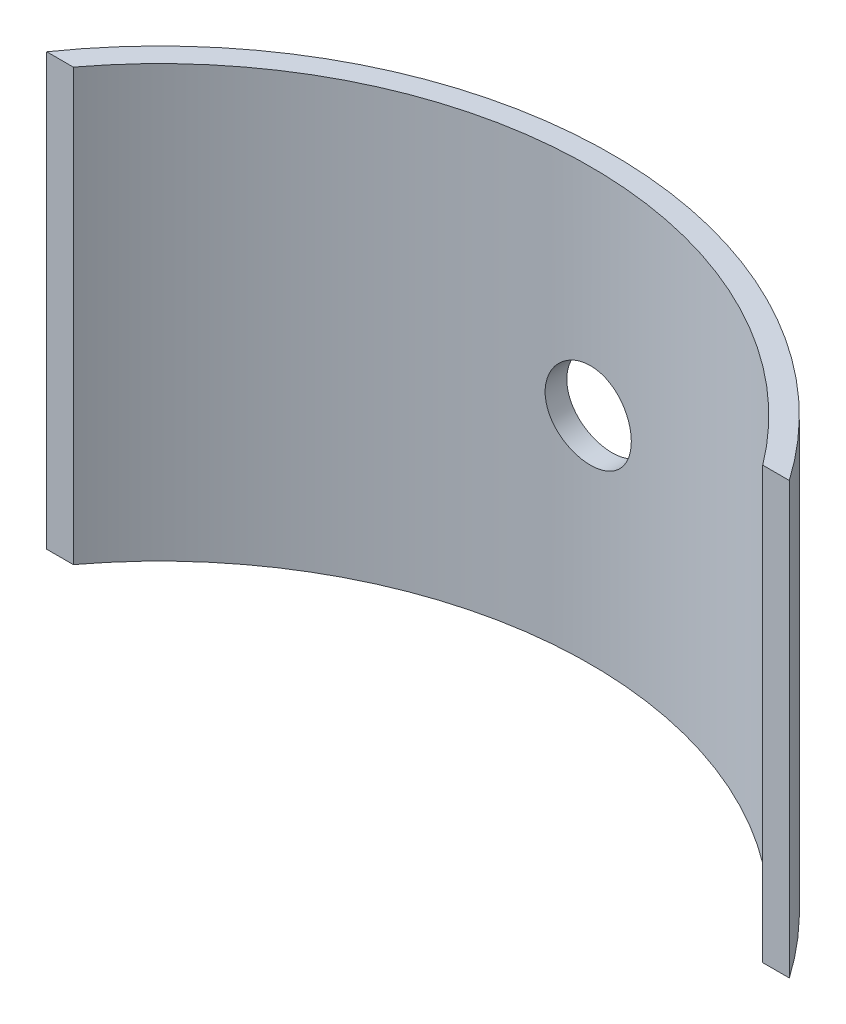
SolidWorks part; units mm, degrees
ref_plane "Front Plane" through (0, 0, 0) normal (0, 0, 1) x (1, 0, 0)
ref_plane "Top Plane" through (0, 0, 0) normal (0, 1, 0) x (1, 0, 0)
ref_plane "Right Plane" through (0, 0, 0) normal (1, 0, 0) x (0, 0, -1)
sketch "Sketch1" plane through (0, 0, 0) normal (0, 1, 0) x (1, 0, 0)
  line L0 (-78.295, 30) -> (78.295, 30) construction
  line L1 (-43.0842, 30) -> (-40, 30)
  line L2 (40, 30) -> (43.0842, 30)
  arc A0 (40, 30) -> (-40, 30) centre (0, 0) ccw
  arc A1 (43.0842, 30) -> (-43.0842, 30) centre (0, 0) ccw
  circle A2 centre (0, 0) radius 52.5 construction
  circle A3 centre (0, 0) radius 50 construction
  point P7 (0, 30)
  dimension "D1" = 100
  dimension "D3" = 30
  dimension "D2" = 2.5
extrude "Boss-Extrude1" add sketch "Sketch1" along normal mid plane 50
ref_plane "Plane1" through (0, 0, -51.25) normal (0, 0, 1) x (1, 0, 0)
sketch "Sketch2" plane through (0, 0, -51.25) normal (0, 0, 1) x (1, 0, 0)
  circle A0 centre (0, 0) radius 5
  point P3 (0, 0)
  dimension "D1" = 10
extrude "Cut-Extrude1" cut sketch "Sketch2" against normal through all both and the other way through all
